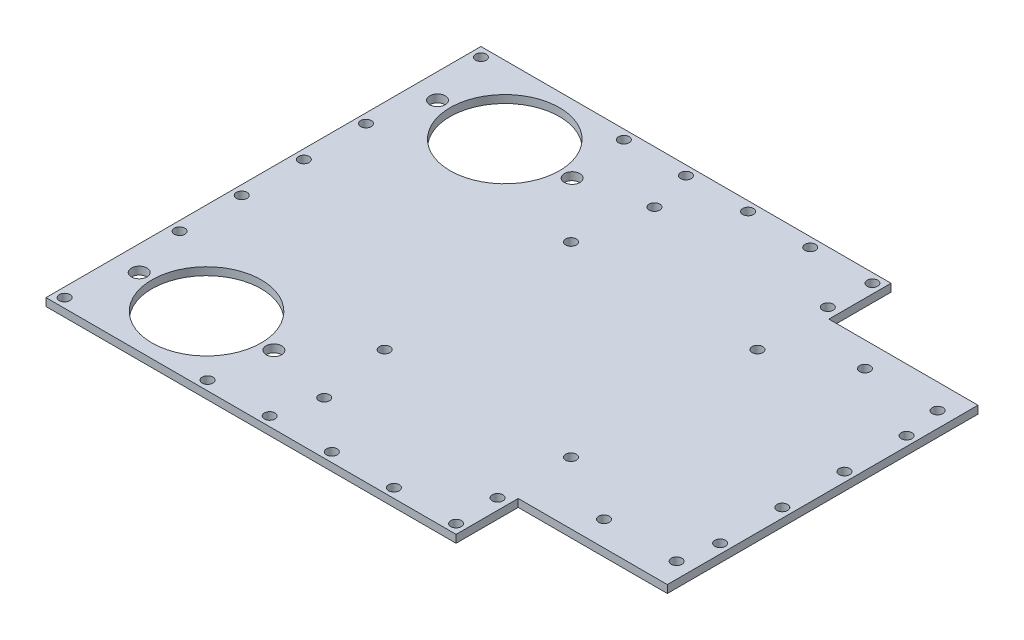
SolidWorks part; units mm, degrees
ref_plane "Front Plane" through (0, 0, 0) normal (0, 0, 1) x (1, 0, 0)
ref_plane "Top Plane" through (0, 0, 0) normal (0, 1, 0) x (1, 0, 0)
ref_plane "Right Plane" through (0, 0, 0) normal (1, 0, 0) x (0, 0, -1)
sketch "Sketch1" plane through (0, 0, 0) normal (0, 1, 0) x (1, 0, 0)
  line L1 (-217.8874, 70.6405) -> (10.7126, 70.6405)
  line L2 (-217.8874, 70.6405) -> (-217.8874, -107.1595)
  line L3 (-217.8874, -107.1595) -> (10.7126, -107.1595)
  line L4 (10.7126, 70.6405) -> (10.7126, -107.1595)
  dimension "D1" = 228.6
  dimension "D2" = 177.8
extrude "Boss-Extrude1" add sketch "Sketch1" along normal blind 3.175
sketch "Sketch2" plane through (0, 3.175, 0) normal (0, 1, 0) x (1, 0, 0)
  line L0 (-217.8874, -107.1595) -> (10.7126, -107.1595) construction
  line L1 (10.7126, -107.1595) -> (-50.2474, -107.1595)
  line L2 (10.7126, -107.1595) -> (10.7126, -81.7595)
  line L3 (10.7126, -81.7595) -> (-50.2474, -81.7595)
  line L4 (-50.2474, -107.1595) -> (-50.2474, -81.7595)
  line L5 (10.7126, -107.1595) -> (10.7126, 70.6405) construction
  line L6 (10.7126, 70.6405) -> (-217.8874, 70.6405) construction
  line L7 (10.7126, 70.6405) -> (-50.2474, 70.6405)
  line L8 (10.7126, 70.6405) -> (10.7126, 45.2405)
  line L9 (10.7126, 45.2405) -> (-50.2474, 45.2405)
  line L10 (-50.2474, 70.6405) -> (-50.2474, 45.2405)
  line L11 (-217.8874, 70.6405) -> (-217.8874, -107.1595) construction
  circle A0 centre (4.3626, 35.0805) radius 2.1717
  circle A1 centre (-25.3554, 35.0805) radius 2.1717
  circle A2 centre (4.3626, -71.5995) radius 2.1717
  circle A3 centre (-25.3554, -71.5995) radius 2.1717
  circle A4 centre (-207.7274, 42.7005) radius 3.175
  circle A5 centre (-152.6602, 42.7005) radius 3.175
  circle A6 centre (-180.1938, 42.7005) radius 22.352
  circle A7 centre (-207.7274, -79.2195) radius 3.175
  circle A8 centre (-180.1938, -79.2195) radius 22.352
  circle A9 centre (-152.6602, -79.2195) radius 3.175
  circle A10 centre (-54.6924, 49.2405) radius 2.1717
  circle A11 centre (-125.5584, 49.2405) radius 2.1717
  circle A12 centre (-125.5584, -85.7595) radius 2.1717
  circle A13 centre (-54.6924, -85.7595) radius 2.1717
  circle A14 centre (-54.0574, 66.8305) radius 2.159
  circle A15 centre (-54.0574, -103.3495) radius 2.159
  circle A16 centre (-214.0774, 66.8305) radius 2.159
  circle A17 centre (-214.0774, -103.3495) radius 2.1717
  circle A18 centre (-79.4574, 66.8305) radius 2.1717
  circle A19 centre (-104.8574, 66.8305) radius 2.1717
  circle A20 centre (-130.2574, 66.8305) radius 2.1717
  circle A21 centre (-155.6574, 66.8305) radius 2.1717
  circle A22 centre (-79.4574, -103.3495) radius 2.1717
  circle A23 centre (-104.8574, -103.3495) radius 2.1717
  circle A24 centre (-130.2574, -103.3495) radius 2.1717
  circle A25 centre (-155.6574, -103.3495) radius 2.1717
  circle A26 centre (-214.0774, 19.8405) radius 2.1717
  circle A27 centre (-214.0774, -5.5595) radius 2.1717
  circle A28 centre (-214.0774, -30.9595) radius 2.1717
  circle A29 centre (-214.0774, -56.3595) radius 2.1717
  circle A30 centre (-130.2574, 19.8405) radius 2.1717
  circle A31 centre (-130.2574, -56.3595) radius 2.1717
  circle A32 centre (6.9026, 19.8405) radius 2.1717
  circle A33 centre (6.9026, -5.5595) radius 2.1717
  circle A34 centre (6.9026, -30.9595) radius 2.1717
  circle A35 centre (6.9026, -56.3595) radius 2.1717
  circle A36 centre (-54.0574, 19.8405) radius 2.1717
  circle A37 centre (-54.0574, -56.3595) radius 2.1717
  point P93 (0, 0)
  dimension "D5" = 6.35
  dimension "D7" = 10.16
  dimension "D9" = 6.35
  dimension "D11" = 29.718
  dimension "D13" = 27.94
  dimension "D15" = 55.0672
  dimension "D17" = 10.16
  dimension "D19" = 27.5336
  dimension "D20" = 55.0672
  dimension "D21" = 21.4
  dimension "D22" = 70.866
  dimension "D24" = 135
  dimension "D25" = 3.81
  dimension "D27" = 3.81
  dimension "D30" = 3.81
  dimension "D32" = 3.81
  dimension "D34" = 25.4
  dimension "D35" = 25.4
  dimension "D38" = 25.4
  dimension "D40" = 25.4
  dimension "D42" = 3.81
  dimension "D44" = 25.4
  dimension "D46" = 25.4
  dimension "D48" = 25.4
  dimension "D50" = 46.99
  dimension "D52" = 25.4
  dimension "D53" = 25.4
  dimension "D54" = 25.4
  dimension "D55" = 46.99
  dimension "D57" = 46.99
  dimension "D59" = 3.81
  dimension "D60" = 25.4
  dimension "D61" = 25.4
  dimension "D62" = 25.4
  dimension "D66" = 46.99
  dimension "D68" = 60.96
  dimension "D1" = 25.4
  dimension "D2" = 60.96
  dimension "D3" = 60.96
  dimension "D4" = 25.4
  dimension "D6" = 10.16
  dimension "D8" = 29.718
  dimension "D10" = 10.16
  dimension "D12" = 10.16
  dimension "D14" = 10.16
  dimension "D16" = 27.5336
  dimension "D18" = 27.94
  dimension "D23" = 4.445
  dimension "D26" = 3.81
  dimension "D28" = 3.81
  dimension "D29" = 70.866
  dimension "D31" = 3.81
  dimension "D33" = 3.81
  dimension "D36" = 3.81
  dimension "D37" = 3.81
  dimension "D39" = 3.81
  dimension "D41" = 3.81
  dimension "D43" = 25.4
  dimension "D45" = 3.81
  dimension "D47" = 3.81
  dimension "D49" = 3.81
  dimension "D51" = 3.81
  dimension "D56" = 83.82
  dimension "D58" = 83.82
  dimension "D63" = 3.81
  dimension "D64" = 3.81
  dimension "D65" = 3.81
  dimension "D67" = 60.96
  dimension "D69" = 46.99
extrude "Cut-Extrude1" cut sketch "Sketch2" against normal blind 3.175
